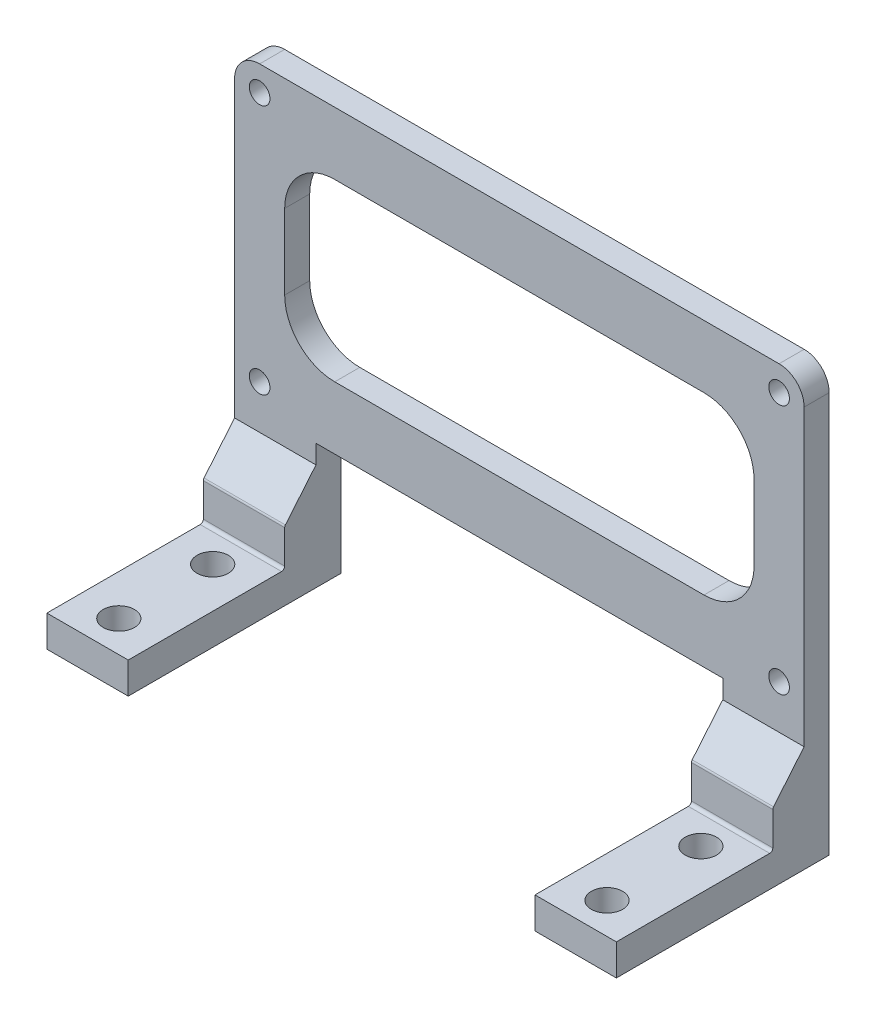
SolidWorks part; units mm, degrees
ref_plane "前视基准面" through (0, 0, 0) normal (0, 0, 1) x (1, 0, 0)
ref_plane "上视基准面" through (0, 0, 0) normal (0, 1, 0) x (1, 0, 0)
ref_plane "右视基准面" through (0, 0, 0) normal (1, 0, 0) x (0, 0, -1)
sketch "草图1" plane through (0, 0, 0) normal (0, 0, 1) x (1, 0, 0)
  line L1 (-45.5, -24) -> (45.5, -24)
  line L2 (-45.5, -24) -> (-45.5, 24)
  line L3 (-45.5, 24) -> (45.5, 24)
  line L4 (45.5, -24) -> (45.5, 24)
  line L5 (-45.5, -24) -> (45.5, 24) construction
  line L6 (-45.5, 24) -> (45.5, -24) construction
  point P0 (0, 0)
  dimension "D1" = 48
  dimension "D2" = 91
extrude "凸台-拉伸1" add sketch "草图1" along normal blind 4
sketch "草图2" plane through (0, 0, 4) normal (0, 0, 1) x (1, 0, 0)
  line L1 (-37.5, -14) -> (37.5, -14)
  line L2 (-37.5, -14) -> (-37.5, 14)
  line L3 (-37.5, 14) -> (37.5, 14)
  line L4 (37.5, -14) -> (37.5, 14)
  line L5 (-37.5, -14) -> (37.5, 14) construction
  line L6 (-37.5, 14) -> (37.5, -14) construction
  point P0 (0, 0)
  dimension "D1" = 75
  dimension "D2" = 28
extrude "切除-拉伸1" cut sketch "草图2" against normal through all
fillet "圆角2" radius 8 4 edges at (-37.5, 14, 2) (-37.5, -14, 2) (37.5, -14, 2) (37.5, 14, 2)
sketch "草图3" plane through (0, 0, 4) normal (0, 0, 1) x (1, 0, 0)
  line L1 (-41.5, -20) -> (41.5, -20) construction
  line L2 (-41.5, -20) -> (-41.5, 20) construction
  line L3 (-41.5, 20) -> (41.5, 20) construction
  line L4 (41.5, -20) -> (41.5, 20) construction
  line L5 (-41.5, -20) -> (41.5, 20) construction
  line L6 (-41.5, 20) -> (41.5, -20) construction
  circle A0 centre (-41.5, 20) radius 1.65
  circle A1 centre (-41.5, -20) radius 1.65
  circle A2 centre (41.5, 20) radius 1.65
  circle A3 centre (41.5, -20) radius 1.65
  point P0 (0, 0)
  dimension "D3" = 3.3
  dimension "D1" = 83
  dimension "D2" = 40
extrude "切除-拉伸2" cut sketch "草图3" against normal through all
sketch "草图5" plane through (0, 0, 0) normal (0, 0, -1) x (-1, 0, 0)
  line L1 (-45.5, -24) -> (-32.5, -24)
  line L2 (-45.5, -24) -> (-45.5, -44)
  line L3 (-45.5, -44) -> (-32.5, -44)
  line L4 (-32.5, -24) -> (-32.5, -44)
  line L5 (45.5, -24) -> (32.5, -24)
  line L6 (45.5, -24) -> (45.5, -44)
  line L7 (45.5, -44) -> (32.5, -44)
  line L8 (32.5, -24) -> (32.5, -44)
  dimension "D1" = 13
  dimension "D2" = 20
extrude "凸台-拉伸2" add sketch "草图5" against normal blind 4
sketch "草图6" plane through (0, 0, 4) normal (0, 0, 1) x (1, 0, 0)
  line L0 (-45.5, 24) -> (-45.5, -44) construction
  line L1 (-32.5, -44) -> (-45.5, -44)
  line L2 (-32.5, -44) -> (-32.5, -39)
  line L3 (-32.5, -39) -> (-45.5, -39)
  line L4 (-45.5, -44) -> (-45.5, -39)
  line L5 (45.5, -44) -> (45.5, 24) construction
  line L6 (32.5, -44) -> (45.5, -44)
  line L7 (32.5, -44) -> (32.5, -39)
  line L8 (32.5, -39) -> (45.5, -39)
  line L9 (45.5, -44) -> (45.5, -39)
  dimension "D1" = 5
extrude "凸台-拉伸3" add sketch "草图6" along normal blind 30
sketch "草图7" plane through (45.5, 0, 0) normal (1, 0, 0) x (0, 0, -1)
  line L0 (-4, -27) -> (-14, -39)
  line L1 (-4, -39) -> (-4, 24) construction
  line L2 (-34, -39) -> (-4, -39) construction
  line L3 (-14, -39) -> (-4, -39)
  line L4 (-4, -39) -> (-4, -27)
  dimension "D1" = 10
  dimension "D2" = 12
extrude "凸台-拉伸4" add sketch "草图7" against normal blind 13
mirror "镜向2" about plane through (0, 0, 0) normal (1, 0, 0) of "凸台-拉伸4"
sketch "草图8" plane through (0, -44, 0) normal (0, -1, 0) x (1, 0, 0)
  line L0 (0, 0) -> (0, 29) construction
  line L1 (-32.5, 0) -> (32.5, 0) construction
  line L2 (-39, 29) -> (39, 29) construction
  line L3 (-39, 14) -> (39, 14) construction
  line L4 (32.5, 34) -> (45.5, 34) construction
  line L5 (39, 0) -> (39, 14) construction
  line L6 (45.5, 0) -> (32.5, 0) construction
  circle A0 centre (39, 29) radius 2.5
  circle A1 centre (-39, 29) radius 2.5
  circle A2 centre (39, 14) radius 2.5
  circle A3 centre (-39, 14) radius 2.5
  point P6 (0, 29)
  point P14 (0, 14)
  point P17 (0, 0)
  dimension "D1" = 5
  dimension "D2" = 15
  dimension "D3" = 5
extrude "切除-拉伸3" cut sketch "草图8" against normal blind 30
sketch "草图9" plane through (-45.5, 0, 0) normal (-1, 0, 0) x (0, 0, 1)
  line L0 (9, -33) -> (9, -39)
  line L1 (4, -27) -> (14, -39) construction
  line L2 (9, -39) -> (14, -39)
  line L3 (14, -39) -> (9, -33)
  point P6 (10.222, -39.8286)
  dimension "D1" = 5
extrude "切除-拉伸4" cut sketch "草图9" against normal through all
fillet "圆角3" radius 0.5 4 edges at (39, -39, 9) (39, -33, 9) (-39, -39, 9) (-39, -33, 9)
fillet "圆角4" radius 4 2 edges at (45.5, 24, 2) (-45.5, 24, 2)
